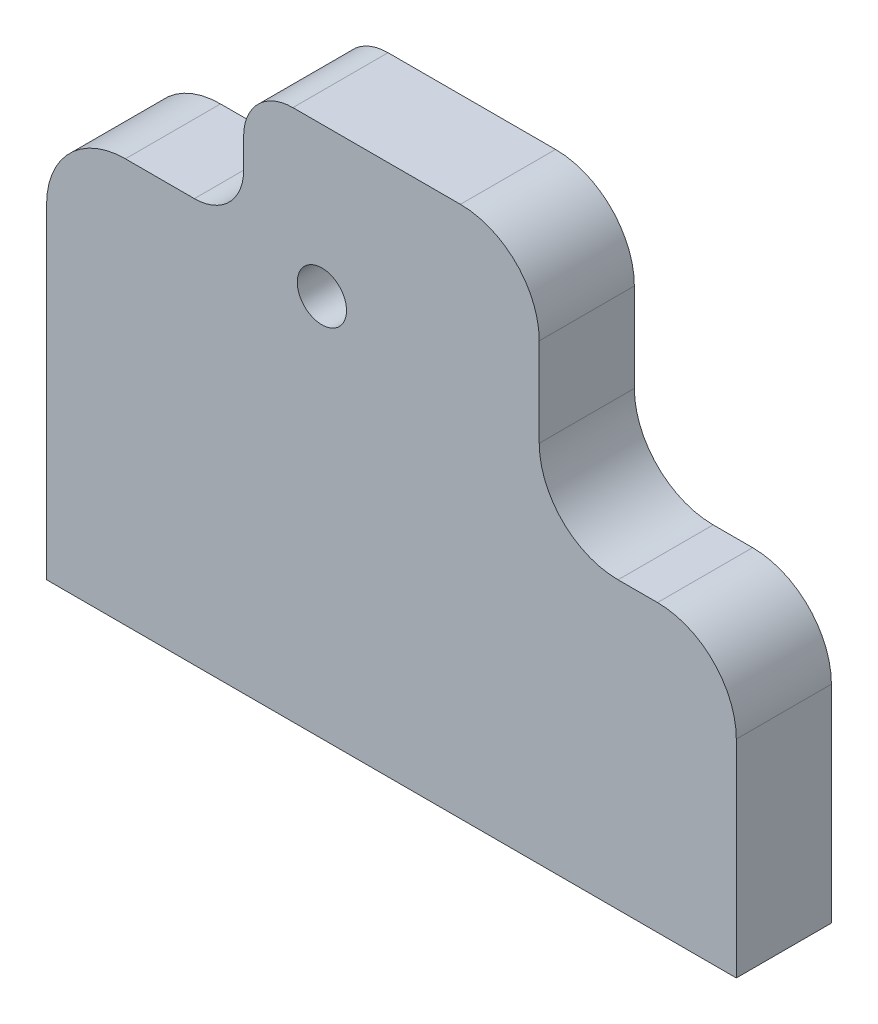
SolidWorks part; units mm, degrees
material "6061 Alloy"
ref_plane "Front" through (0, 0, 0) normal (0, 0, 1) x (1, 0, 0)
ref_plane "Top" through (0, 0, 0) normal (0, 1, 0) x (1, 0, 0)
ref_plane "Right" through (0, 0, 0) normal (1, 0, 0) x (0, 0, -1)
sketch "Sketch1" plane through (0, 0, 0) normal (0, 0, 1) x (1, 0, 0)
  line L0 (0, 0) -> (0, 13.5)
  line L9 (35, 0) -> (0, 0)
  line L15 (10, 20) -> (25, 20)
  line L16 (25, 20) -> (25, 7.5)
  line L17 (25, 7.5) -> (35, 7.5)
  line L18 (35, 7.5) -> (35, 0)
  line L20 (0, 13.5) -> (10, 13.5)
  line L21 (10, 13.5) -> (10, 20)
  dimension "D3" = 13.5
  dimension "D1" = 35
  dimension "D2" = 10
  dimension "D4" = 15
  dimension "D5" = 20
  dimension "D6" = 7.5
extrude "Boss-Extrude1" add sketch "Sketch1" along normal blind 4.826
hole_wizard "M3x0.5 Tapped Hole2" positions "Sketch13" profile "Sketch14" tap size "M3x0.5" standard "ANSI Metric" end condition through all
sketch "Sketch13" plane through (0, 0, 4.826) normal (0, 0, 1) x (1, 0, 0)
  line L2 (35, 0) -> (0, 0) construction
  point P5 (13.9702, 12.44)
  dimension "D1" = 12.44
  dimension "D2" = 13.9702
sketch "Sketch14" plane through (13.9702, 12.44, 4.826) normal (1, 0, 0) x (0, -1, 0)
  line L0 (0, 0) -> (0, 4.826)
  line L1 (0, 4.826) -> (1.25, 4.826)
  line L2 (1.25, 4.826) -> (1.25, 0)
  line L5 (1.25, 0) -> (0, 0)
  line L11 (0, -6.35) -> (0, 107.95) construction
  dimension "Thru Tap Drill Dia." = 2.5
  dimension "Thru Tap Drill Depth" = 4.826
cosmetic thread "Hole Thread1" parameters "D2"=3
sketch "Sketch16" plane through (0, 0, 0) normal (0, -1, 0) x (1, 0, 0)
  line L0 (0, 4.826) -> (0, 0) construction
  line L3 (0, 2.413) -> (42.6944, 2.413) construction
  point P0 (28.73, 2.413)
  point P1 (16.73, 2.413)
  dimension "D1" = 16.73
  dimension "D2" = 12
hole_wizard "M3x0.5 Tapped Hole3" positions "Sketch17" profile "Sketch18" tap size "M3x0.5" standard "ANSI Metric"
sketch "Sketch17" plane through (0, 0, 0) normal (0, -1, 0) x (-1, 0, 0)
  point P0 (-16.73, -2.413)
  point P3 (-28.73, -2.413)
sketch "Sketch18" plane through (16.73, 0, 2.413) normal (1, 0, 0) x (0, 0, -1)
  line L0 (0, 0) -> (0, 5.7511)
  line L1 (0, 5.7511) -> (1.25, 5)
  line L2 (1.25, 5) -> (1.25, 0)
  line L5 (1.25, 0) -> (0, 0)
  line L10 (0, 5.7511) -> (-1.25, 5) construction
  line L11 (0, -6.35) -> (0, 107.95) construction
  dimension "Tap Drill Dia." = 2.5
  dimension "Tap Drill Depth" = 5
  dimension "Drill Angle" = 118
fillet "Fillet1" radius 2.5 2 edges at (10, 13.5, 2.413) (10, 20, 2.413)
chamfer "Chamfer1" [suppressed] distance 13 distance2 10
fillet "Fillet2" radius 4 4 edges at (35, 7.5, 2.413) (25, 7.5, 2.413) (25, 20, 2.413) (0, 13.5, 2.413)
sketch "Sketch20" plane through (0, 0, 0) normal (0, -1, 0) x (1, 0, 0)
  line L1 (0, 0) -> (35, 0)
  line L2 (0, 0) -> (0, 4.826)
  line L3 (0, 4.826) -> (35, 4.826)
  line L4 (35, 0) -> (35, 4.826)
  circle A0 centre (28.73, 2.413) radius 1.25
  circle A1 centre (16.73, 2.413) radius 1.25
extrude "Boss-Extrude2" add sketch "Sketch20" along normal blind 7
